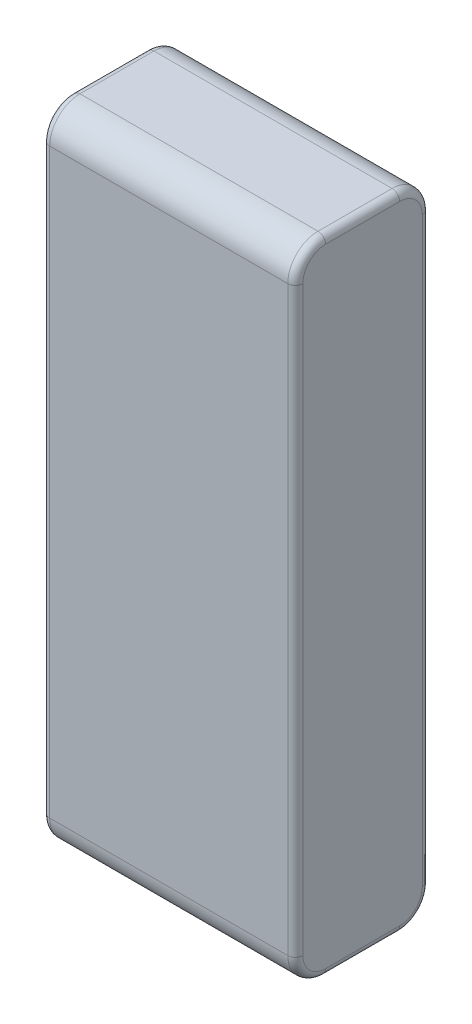
SolidWorks part; units mm, degrees
ref_plane "Front Plane" through (0, 0, 0) normal (0, 0, 1) x (1, 0, 0)
ref_plane "Top Plane" through (0, 0, 0) normal (0, 1, 0) x (1, 0, 0)
ref_plane "Right Plane" through (0, 0, 0) normal (1, 0, 0) x (0, 0, -1)
sketch "Sketch1" plane through (0, 0, 0) normal (0, 0, 1) x (1, 0, 0)
  line L1 (-16.75, -42.5) -> (16.75, -42.5)
  line L2 (-16.75, -42.5) -> (-16.75, 42.5)
  line L3 (-16.75, 42.5) -> (16.75, 42.5)
  line L4 (16.75, -42.5) -> (16.75, 42.5)
  line L5 (-16.75, -42.5) -> (16.75, 42.5) construction
  line L6 (-16.75, 42.5) -> (16.75, -42.5) construction
  point P0 (0, 0)
  dimension "D1" = 33.5
  dimension "D2" = 85
extrude "Boss-Extrude1" add sketch "Sketch1" along normal mid plane 17.8
fillet "Fillet1" radius 4 4 edges at (0, -42.5, -8.9) (0, -42.5, 8.9) (0, 42.5, -8.9) (0, 42.5, 8.9)
fillet "Fillet2" radius 1 16 edges at (-16.75, 41.3284, 7.7284) (-16.75, 42.5, 0) (-16.75, 41.3284, -7.7284) (-16.75, 0, -8.9) (-16.75, -41.3284, -7.7284) (-16.75, -42.5, 0) (-16.75, -41.3284, 7.7284) (16.75, -41.3284, 7.7284) (16.75, 0, 8.9) (16.75, 41.3284, 7.7284) (16.75, 42.5, 0) (16.75, 41.3284, -7.7284) (16.75, 0, -8.9) (16.75, -41.3284, -7.7284) (16.75, -42.5, 0) (-16.75, 0, 8.9)
